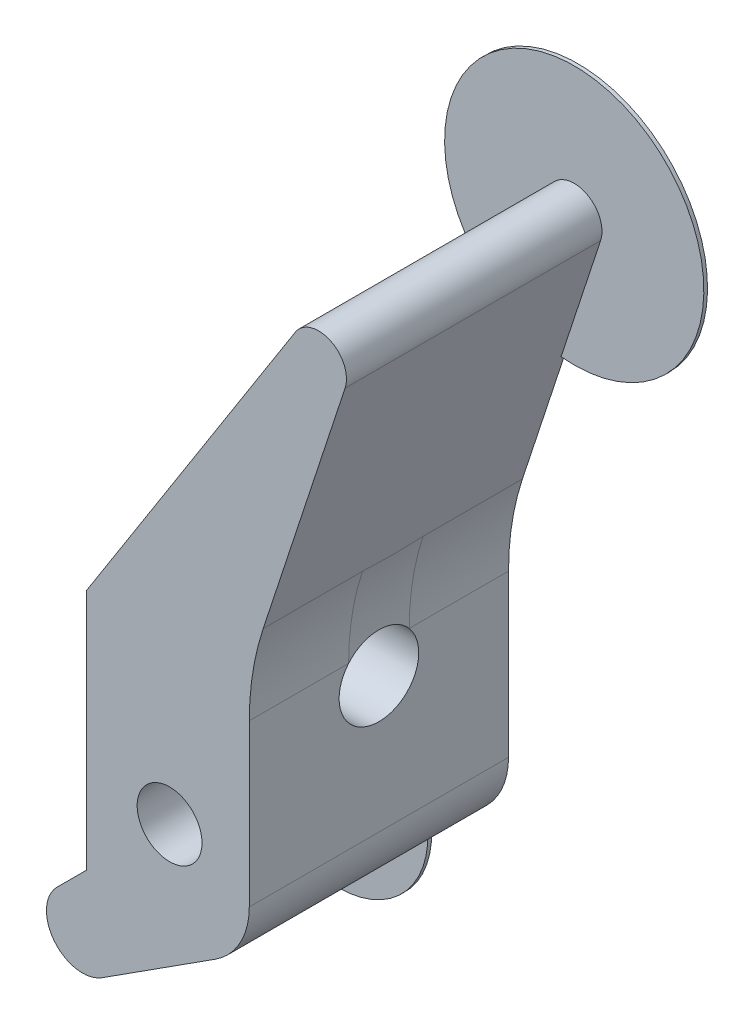
SolidWorks part; units mm, degrees
ref_plane "Front Plane" through (0, 0, 0) normal (0, 0, 1) x (1, 0, 0)
ref_plane "Top Plane" through (0, 0, 0) normal (0, 1, 0) x (1, 0, 0)
ref_plane "Right Plane" through (0, 0, 0) normal (1, 0, 0) x (0, 0, -1)
ref_plane "Plane1" through (0, 0, 36.06) normal (0, 0, 1) x (1, 0, 0)
sketch "Sketch1" plane through (0, 0, 36.06) normal (0, 0, 1) x (1, 0, 0)
  line L0 (32.4855, 18.0542) -> (21.2, 0.3181)
  line L1 (21.2, 0.3181) -> (21.2, -12.7532)
  line L2 (21.2, -12.7532) -> (19.6211, -14.3321)
  line L3 (22.0528, -17.3523) -> (30.004, -12.2525)
  line L4 (30.004, -12.2525) -> (30.004, 1.0432)
  line L5 (30.004, 1.0432) -> (35.1761, 16.7806)
  arc A0 (35.1761, 16.7806) -> (32.4855, 18.0542) centre (33.7511, 17.249) ccw
  arc A1 (19.6211, -14.3321) -> (22.0528, -17.3523) centre (21, -15.711) ccw
extrude "Boss-Extrude1" add sketch "Sketch1" against normal blind 13.8
sketch "Sketch2" plane through (0, 0, 22.26) normal (0, 0, -1) x (-1, 0, 0)
  line L0 (-28.8149, 12.2856) -> (-21.2, 0.3181)
  line L1 (-21.2, 0.3181) -> (-21.2, -10.8639)
  line L2 (-25.7918, -14.9541) -> (-30.004, -12.2525)
  line L3 (-30.004, -12.2525) -> (-30.004, 1.0432)
  line L4 (-30.004, 1.0432) -> (-33.0413, 10.285)
  arc A0 (-21.2, -10.8639) -> (-25.7918, -14.9541) centre (-21, -15.711) cw
  arc A1 (-33.0413, 10.285) -> (-28.8149, 12.2856) centre (-33.7511, 17.249) cw
extrude "Boss-Extrude2" add sketch "Sketch2" along normal blind 0.2
sketch "Sketch3" plane through (21.2, 0, 0) normal (-1, 0, 0) x (0, 0, 1)
  line L0 (29.0607, -7.0249) -> (32.7604, -4.888)
  line L1 (32.7604, -4.888) -> (32.7596, -0.6156)
  line L2 (32.7596, -0.6156) -> (29.0593, 1.5199)
  line L3 (29.0593, 1.5199) -> (25.3596, -0.6169)
  line L4 (25.3596, -0.6169) -> (25.3604, -4.8893)
  line L5 (25.3604, -4.8893) -> (29.0607, -7.0249)
  line L6 (32.7596, -0.6156) -> (25.3604, -4.8893) construction
  line L7 (25.3596, -0.6169) -> (32.7604, -4.888) construction
  line L9 (29.0593, 1.5199) -> (29.0607, -7.0249) construction
  line L10 (22.06, -12.2525) -> (36.06, -12.2525) construction
  point P6 (29.06, -2.7525)
  dimension "D1" = 9.5
  dimension "D2" = 120
  dimension "D3" = 120
  dimension "D4" = 120
  dimension "D5" = 120
  dimension "D6" = 120
extrude "Cut-Extrude1" cut sketch "Sketch3" against normal blind 3.4
hole_wizard "Ø3.3 (3.3) Diameter Hole1" positions "Sketch5" profile "Sketch4" hole size "Ø3.3" standard "ANSI Metric"
sketch "Sketch5" plane through (0, 0, 22.06) normal (0, 0, -1) x (-1, 0, 0)
  point P0 (-25.002, -10.5875)
sketch "Sketch4" plane through (25.002, -10.5875, 22.06) normal (1, 0, 0) x (0, 1, 0)
  line L0 (0, 0) -> (0, 14)
  line L1 (0, 14) -> (1.65, 14)
  line L2 (1.65, 14) -> (1.65, 0)
  line L5 (1.65, 0) -> (0, 0)
  line L11 (0, -6.35) -> (0, 107.95) construction
  dimension "Thru Hole Dia." = 3.3
  dimension "Thru Hole Depth" = 14
hole_wizard "Ø4.3 (4.3) Diameter Hole1" positions "Sketch7" profile "Sketch6" hole size "Ø4.3" standard "ANSI Metric" end condition through all
sketch "Sketch7" plane through (24.6, 0, 0) normal (-1, 0, 0) x (0, 0, 1)
  line L0 (22.06, -12.2525) -> (36.06, -12.2525) construction
  point P0 (29.06, -2.7525)
  dimension "D1" = 9.5
sketch "Sketch6" plane through (24.6, -2.7525, 29.06) normal (0, 1, 0) x (0, 0, 1)
  line L0 (0, 0) -> (0, 16.151)
  line L1 (0, 16.151) -> (2.15, 16.151)
  line L2 (2.15, 16.151) -> (2.15, 0)
  line L5 (2.15, 0) -> (0, 0)
  line L11 (0, -6.35) -> (0, 107.95) construction
  dimension "Thru Hole Dia." = 4.3
  dimension "Thru Hole Depth" = 16.151
fillet "Fillet1" radius 3 1 edges at (21.2, 0.3181, 24.5192)
fillet "Fillet2" radius 4 1 edges at (30.004, -12.2525, 29.06)
fillet "Fillet3" radius 15 1 edges at (30.004, 1.0432, 29.06)
sketch "Sketch8" plane through (0, 0, 36.06) normal (0, 0, 1) x (1, 0, 0)
  line L0 (21.2, 0.3181) -> (21.2, -12.7532) construction
  circle A0 centre (25.7, -8.3523) radius 1.75
  point P6 (23.3902, -8.4966)
  dimension "D1" = 3.5
  dimension "D2" = 4.5
  dimension "D3" = 9
extrude "Cut-Extrude2" cut sketch "Sketch8" against normal through all
